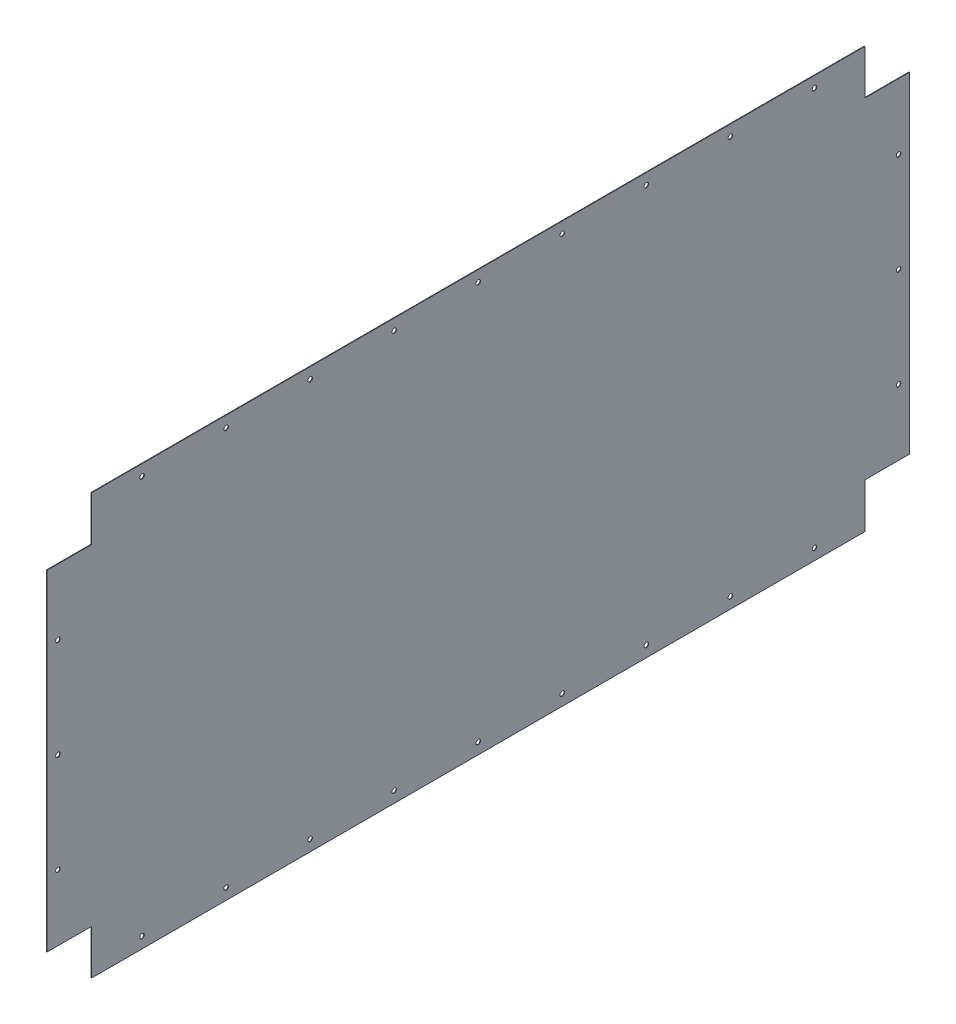
SolidWorks part; units mm, degrees
ref_plane "Front Plane" through (0, 0, 0) normal (0, 0, 1) x (1, 0, 0)
ref_plane "Top Plane" through (0, 0, 0) normal (0, 1, 0) x (1, 0, 0)
ref_plane "Right Plane" through (0, 0, 0) normal (1, 0, 0) x (0, 0, -1)
sketch "Sketch1" plane through (0, 0, 0) normal (1, 0, 0) x (0, 0, -1)
  line L0 (-759.96, 179.99) -> (759.96, 179.99) construction
  line L1 (-779.96, 379.98) -> (779.96, 379.98)
  line L2 (-779.96, 379.98) -> (-779.96, -379.98)
  line L3 (-779.96, -379.98) -> (779.96, -379.98)
  line L4 (779.96, 379.98) -> (779.96, -379.98)
  line L5 (-779.96, 379.98) -> (779.96, -379.98) construction
  line L6 (-779.96, -379.98) -> (779.96, 379.98) construction
  line L7 (-759.96, 359.98) -> (759.96, 359.98) construction
  line L8 (-759.96, 359.98) -> (-759.96, -359.98) construction
  line L9 (-759.96, -359.98) -> (759.96, -359.98) construction
  line L10 (759.96, 359.98) -> (759.96, -359.98) construction
  line L11 (-759.96, 359.98) -> (759.96, -359.98) construction
  line L12 (-759.96, -359.98) -> (759.96, 359.98) construction
  line L13 (759.96, 179.99) -> (-759.96, -179.99) construction
  line L14 (-759.96, -179.99) -> (759.96, -179.99) construction
  line L15 (-759.96, 0) -> (0, 0) construction
  line L16 (0, 179.99) -> (0, 0) construction
  line L17 (0, 0) -> (0, -179.99) construction
  line L18 (0, -179.99) -> (-0.01, -359.98) construction
  line L19 (-0.01, 359.98) -> (0, 179.99) construction
  circle A0 centre (-759.96, 359.98) radius 4.1
  circle A1 centre (-759.96, -359.98) radius 4.1
  circle A2 centre (-607.97, 359.98) radius 4.1
  circle A3 centre (-607.97, -359.98) radius 4.1
  circle A4 centre (-455.98, 359.98) radius 4.1
  circle A5 centre (-455.98, -359.98) radius 4.1
  circle A6 centre (-303.99, 359.98) radius 4.1
  circle A7 centre (-303.99, -359.98) radius 4.1
  circle A8 centre (-152, 359.98) radius 4.1
  circle A9 centre (-152, -359.98) radius 4.1
  circle A10 centre (-0.01, 359.98) radius 4.1
  circle A11 centre (-0.01, -359.98) radius 4.1
  circle A12 centre (151.98, 359.98) radius 4.1
  circle A13 centre (151.98, -359.98) radius 4.1
  circle A14 centre (303.97, 359.98) radius 4.1
  circle A15 centre (303.97, -359.98) radius 4.1
  circle A16 centre (455.96, 359.98) radius 4.1
  circle A17 centre (455.96, -359.98) radius 4.1
  circle A18 centre (607.95, 359.98) radius 4.1
  circle A19 centre (607.95, -359.98) radius 4.1
  circle A20 centre (759.94, 359.98) radius 4.1
  circle A21 centre (759.94, -359.98) radius 4.1
  circle A22 centre (-759.96, 179.99) radius 4.1
  circle A23 centre (-759.96, 0) radius 4.1
  circle A24 centre (-759.96, -179.99) radius 4.1
  circle A25 centre (759.96, 0) radius 4.1
  circle A26 centre (759.96, 179.99) radius 4.1
  circle A27 centre (759.96, -179.99) radius 4.1
  point P0 (0, 0)
  point P6 (0, 0)
  dimension "D5" = 8.2
  dimension "D1" = 1519.92
  dimension "D2" = 719.96
  dimension "D3" = 20
  dimension "D4" = 20
  dimension "D6" = 11
extrude "Boss-Extrude1" add sketch "Sketch1" along normal blind 1
sketch "Sketch2" plane through (0, 0, 0) normal (1, 0, 0) x (0, 0, -1)
  line L1 (-739.46, -339.48) -> (739.46, -339.48) construction
  line L2 (-739.46, -339.48) -> (-739.46, 339.48) construction
  line L3 (-739.46, 339.48) -> (739.46, 339.48) construction
  line L4 (739.46, -339.48) -> (739.46, 339.48) construction
  line L5 (-739.46, -339.48) -> (739.46, 339.48) construction
  line L6 (-739.46, 339.48) -> (739.46, -339.48) construction
  line L7 (-779.96, 298.98) -> (-698.96, 298.98)
  line L8 (-779.96, 298.98) -> (-779.96, 379.98)
  line L9 (-779.96, 379.98) -> (-698.96, 379.98)
  line L10 (-698.96, 298.98) -> (-698.96, 379.98)
  line L11 (-779.96, 298.98) -> (-698.96, 379.98) construction
  line L12 (-779.96, 379.98) -> (-698.96, 298.98) construction
  line L13 (-779.96, -298.98) -> (-698.96, -298.98)
  line L14 (-779.96, -298.98) -> (-779.96, -379.98)
  line L15 (-779.96, -379.98) -> (-698.96, -379.98)
  line L16 (-698.96, -298.98) -> (-698.96, -379.98)
  line L17 (-779.96, -298.98) -> (-698.96, -379.98) construction
  line L18 (-779.96, -379.98) -> (-698.96, -298.98) construction
  line L19 (698.96, -298.98) -> (779.96, -298.98)
  line L20 (698.96, -298.98) -> (698.96, -379.98)
  line L21 (698.96, -379.98) -> (779.96, -379.98)
  line L22 (779.96, -298.98) -> (779.96, -379.98)
  line L23 (698.96, -298.98) -> (779.96, -379.98) construction
  line L24 (698.96, -379.98) -> (779.96, -298.98) construction
  line L25 (698.96, 298.98) -> (779.96, 298.98)
  line L26 (698.96, 298.98) -> (698.96, 379.98)
  line L27 (698.96, 379.98) -> (779.96, 379.98)
  line L28 (779.96, 298.98) -> (779.96, 379.98)
  line L29 (698.96, 298.98) -> (779.96, 379.98) construction
  line L30 (698.96, 379.98) -> (779.96, 298.98) construction
  point P0 (0, 0)
  point P22 (-779.96, 379.98)
  dimension "D1" = 81
extrude "Cut-Extrude1" cut sketch "Sketch2" against normal blind 10 and the other way blind 10
